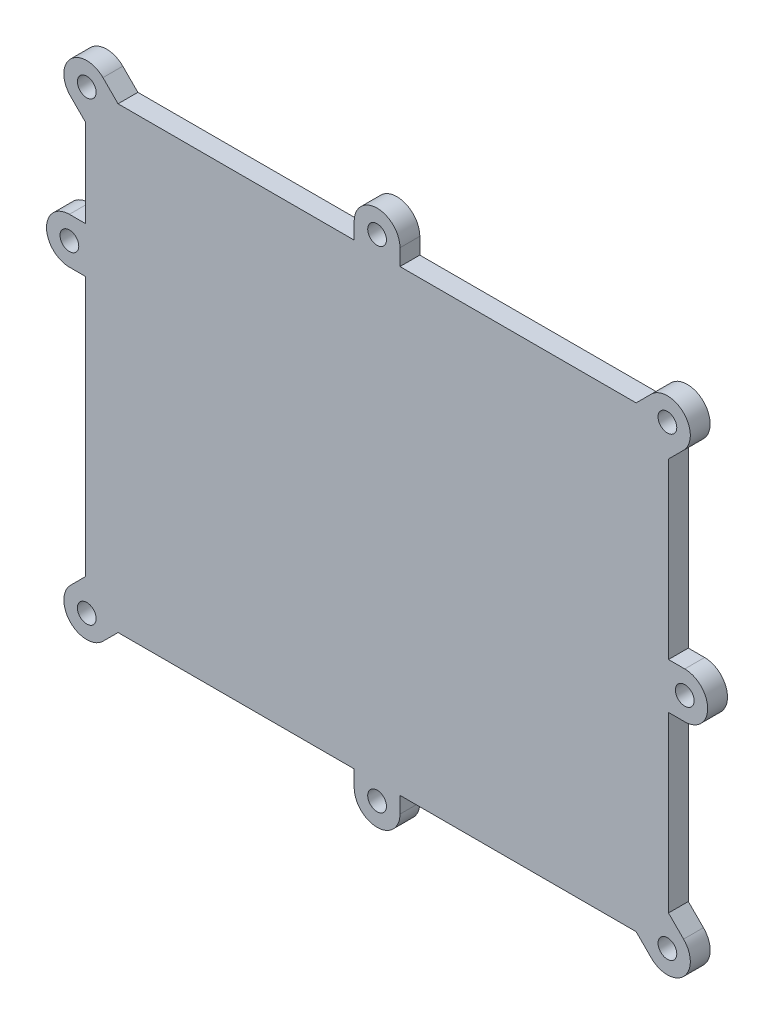
SolidWorks part; units mm, degrees
material "Acrylic (Medium-high impact)"
ref_plane "X-Y Datum" through (0, 0, 0) normal (0, 0, 1) x (1, 0, 0)
ref_plane "X-Z Datum" through (0, 0, 0) normal (0, 1, 0) x (1, 0, 0)
ref_plane "Y-Z Datum" through (0, 0, 0) normal (1, 0, 0) x (0, 0, -1)
sketch "Sketch1" plane through (0, 0, 0) normal (0, 0, 1) x (1, 0, 0)
  line L126 (0, -13.447) -> (0, -33.5299)
  line L129 (0, -51.5028) -> (0, -107.8906)
  line L130 (0, -107.8906) -> (-3.6269, -111.5175)
  line L131 (4.1513, -119.2957) -> (7.7782, -115.6688)
  line L132 (7.7782, -115.6688) -> (64.5, -115.6688)
  line L133 (64.5, -115.6688) -> (64.5, -119.5785)
  line L134 (75.5, -119.5785) -> (75.5, -115.6688)
  line L135 (75.5, -115.6688) -> (132.2218, -115.6688)
  line L136 (132.2218, -115.6688) -> (135.8487, -119.2957)
  line L137 (143.6269, -111.5175) -> (140, -107.8906)
  line L138 (140, -107.8906) -> (140, -66.1688)
  line L139 (140, -66.1688) -> (143.9097, -66.1688)
  line L140 (143.9097, -55.1688) -> (140, -55.1688)
  line L141 (140, -55.1688) -> (140, -13.447)
  line L142 (140, -13.447) -> (143.6269, -9.8201)
  line L143 (135.8487, -2.0419) -> (132.2218, -5.6688)
  line L144 (132.2218, -5.6688) -> (75.5, -5.6688)
  line L145 (75.5, -5.6688) -> (75.5, -1.7591)
  line L146 (64.5, -1.7591) -> (64.5, -5.6688)
  line L147 (64.5, -5.6688) -> (7.7782, -5.6688)
  line L148 (7.7782, -5.6688) -> (4.1513, -2.0419)
  line L149 (-3.6269, -9.8201) -> (0, -13.447)
  line L150 (0, -13.447) -> (0, -33.5299)
  line L153 (0, -46.9028) -> (0, -107.8906)
  line L154 (0, -107.8906) -> (-3.6269, -111.5175)
  line L155 (4.1513, -119.2957) -> (7.7782, -115.6688)
  line L156 (7.7782, -115.6688) -> (64.5, -115.6688)
  line L157 (64.5, -115.6688) -> (64.5, -119.5785)
  line L158 (75.5, -119.5785) -> (75.5, -115.6688)
  line L159 (75.5, -115.6688) -> (132.2218, -115.6688)
  line L160 (132.2218, -115.6688) -> (135.8487, -119.2957)
  line L161 (143.6269, -111.5175) -> (140, -107.8906)
  line L162 (140, -107.8906) -> (140, -66.1688)
  line L163 (140, -66.1688) -> (143.9097, -66.1688)
  line L164 (143.9097, -55.1688) -> (140, -55.1688)
  line L165 (140, -55.1688) -> (140, -13.447)
  line L166 (140, -13.447) -> (143.6269, -9.8201)
  line L167 (135.8487, -2.0419) -> (132.2218, -5.6688)
  line L168 (132.2218, -5.6688) -> (75.5, -5.6688)
  line L169 (75.5, -5.6688) -> (75.5, -1.7591)
  line L170 (64.5, -1.7591) -> (64.5, -5.6688)
  line L171 (64.5, -5.6688) -> (7.7782, -5.6688)
  line L172 (7.7782, -5.6688) -> (4.1513, -2.0419)
  line L173 (-3.6269, -9.8201) -> (0, -13.447)
  line L222 (0, -13.447) -> (0, -34.5028)
  line L223 (0, -34.5028) -> (-3.9097, -34.5028)
  line L224 (-3.9097, -45.5028) -> (0, -45.5028)
  line L225 (0, -45.5028) -> (0, -107.8906)
  line L226 (0, -107.8906) -> (-3.6269, -111.5175)
  line L227 (4.1513, -119.2957) -> (7.7782, -115.6688)
  line L228 (7.7782, -115.6688) -> (64.5, -115.6688)
  line L229 (64.5, -115.6688) -> (64.5, -119.5785)
  line L230 (75.5, -119.5785) -> (75.5, -115.6688)
  line L231 (75.5, -115.6688) -> (132.2218, -115.6688)
  line L232 (132.2218, -115.6688) -> (135.8487, -119.2957)
  line L233 (143.6269, -111.5175) -> (140, -107.8906)
  line L234 (140, -107.8906) -> (140, -66.1688)
  line L235 (140, -66.1688) -> (143.9097, -66.1688)
  line L236 (143.9097, -55.1688) -> (140, -55.1688)
  line L237 (140, -55.1688) -> (140, -13.447)
  line L238 (140, -13.447) -> (143.6269, -9.8201)
  line L239 (135.8487, -2.0419) -> (132.2218, -5.6688)
  line L240 (132.2218, -5.6688) -> (75.5, -5.6688)
  line L241 (75.5, -5.6688) -> (75.5, -1.7591)
  line L242 (64.5, -1.7591) -> (64.5, -5.6688)
  line L243 (64.5, -5.6688) -> (7.7782, -5.6688)
  line L244 (7.7782, -5.6688) -> (4.1513, -2.0419)
  line L245 (-3.6269, -9.8201) -> (0, -13.447)
  arc A43 (-3.6269, -111.5175) -> (4.1513, -119.2957) centre (0.2622, -115.4066) ccw
  arc A44 (64.5, -119.5785) -> (75.5, -119.5785) centre (70, -119.5785) ccw
  arc A45 (135.8487, -119.2957) -> (143.6269, -111.5175) centre (139.7378, -115.4066) ccw
  arc A46 (143.9097, -66.1688) -> (143.9097, -55.1688) centre (143.9097, -60.6688) ccw
  arc A47 (143.6269, -9.8201) -> (135.8487, -2.0419) centre (139.7378, -5.931) ccw
  arc A48 (75.5, -1.7591) -> (64.5, -1.7591) centre (70, -1.7591) ccw
  arc A49 (4.1513, -2.0419) -> (-3.6269, -9.8201) centre (0.2622, -5.931) ccw
  arc A51 (-3.6269, -111.5175) -> (4.1513, -119.2957) centre (0.2622, -115.4066) ccw
  arc A52 (64.5, -119.5785) -> (75.5, -119.5785) centre (70, -119.5785) ccw
  arc A53 (135.8487, -119.2957) -> (143.6269, -111.5175) centre (139.7378, -115.4066) ccw
  arc A54 (143.9097, -66.1688) -> (143.9097, -55.1688) centre (143.9097, -60.6688) ccw
  arc A55 (143.6269, -9.8201) -> (135.8487, -2.0419) centre (139.7378, -5.931) ccw
  arc A56 (75.5, -1.7591) -> (64.5, -1.7591) centre (70, -1.7591) ccw
  arc A57 (4.1513, -2.0419) -> (-3.6269, -9.8201) centre (0.2622, -5.931) ccw
  arc A74 (-3.9097, -34.5028) -> (-3.9097, -45.5028) centre (-3.9097, -40.0028) ccw
  arc A75 (-3.6269, -111.5175) -> (4.1513, -119.2957) centre (0.2622, -115.4066) ccw
  arc A76 (64.5, -119.5785) -> (75.5, -119.5785) centre (70, -119.5785) ccw
  arc A77 (135.8487, -119.2957) -> (143.6269, -111.5175) centre (139.7378, -115.4066) ccw
  arc A78 (143.9097, -66.1688) -> (143.9097, -55.1688) centre (143.9097, -60.6688) ccw
  arc A79 (143.6269, -9.8201) -> (135.8487, -2.0419) centre (139.7378, -5.931) ccw
  arc A80 (75.5, -1.7591) -> (64.5, -1.7591) centre (70, -1.7591) ccw
  arc A81 (4.1513, -2.0419) -> (-3.6269, -9.8201) centre (0.2622, -5.931) ccw
extrude "Boss-Extrude1" add sketch "Sketch1" along normal blind 4.7625
hole_wizard "M4 Clearance Hole1" positions "Sketch2" profile "Sketch3" hole size "M4" standard "ANSI Metric" end condition through all
sketch "Sketch2" plane through (0, 0, 4.7625) normal (0, 0, 1) x (1, 0, 0)
  point P0 (0.2622, -5.931)
  point P2 (-3.9097, -40.0028)
  point P4 (0.2622, -115.4066)
  point P6 (70, -119.5785)
  point P8 (139.7378, -115.4066)
  point P10 (143.9097, -60.6688)
  point P12 (139.7378, -5.931)
  point P14 (70, -1.7591)
  point P20 (-3.9097, -40.0028)
sketch "Sketch3" plane through (0.2622, -5.931, 4.7625) normal (1, 0, 0) x (0, -1, 0)
  line L0 (0, 0) -> (0, 4.7625)
  line L1 (0, 4.7625) -> (2.25, 4.7625)
  line L2 (2.25, 4.7625) -> (2.25, 0)
  line L5 (2.25, 0) -> (0, 0)
  line L11 (0, -6.35) -> (0, 107.95) construction
  dimension "Thru Hole Dia." = 4.5
  dimension "Thru Hole Depth" = 4.7625
